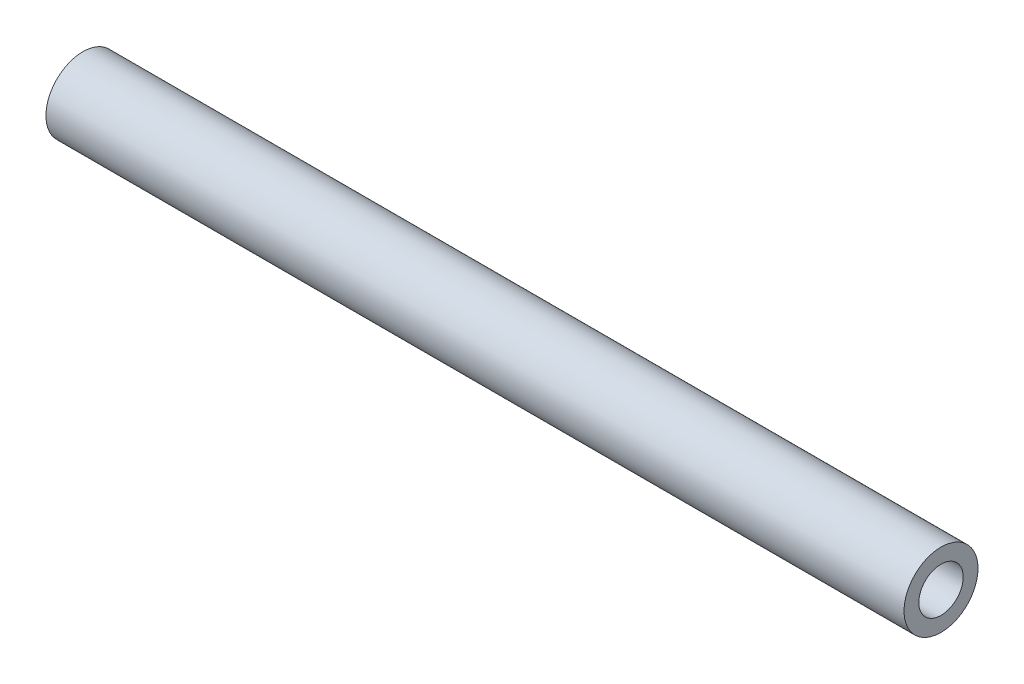
SolidWorks part; units mm, degrees
material "Thornel Mat VMA"
ref_plane "Front Plane" through (0, 0, 0) normal (0, 0, 1) x (1, 0, 0)
ref_plane "Top Plane" through (0, 0, 0) normal (0, 1, 0) x (1, 0, 0)
ref_plane "Right Plane" through (0, 0, 0) normal (1, 0, 0) x (0, 0, -1)
sketch "Sketch1" plane through (0, 0, 0) normal (1, 0, 0) x (0, 0, -1)
  circle A0 centre (0, 0) radius 4.7625
  circle A1 centre (0, 0) radius 7.9375
  dimension "D1" = 9.525
  dimension "D2" = 15.875
extrude "Boss-Extrude1" add sketch "Sketch1" along normal mid plane 184.15
